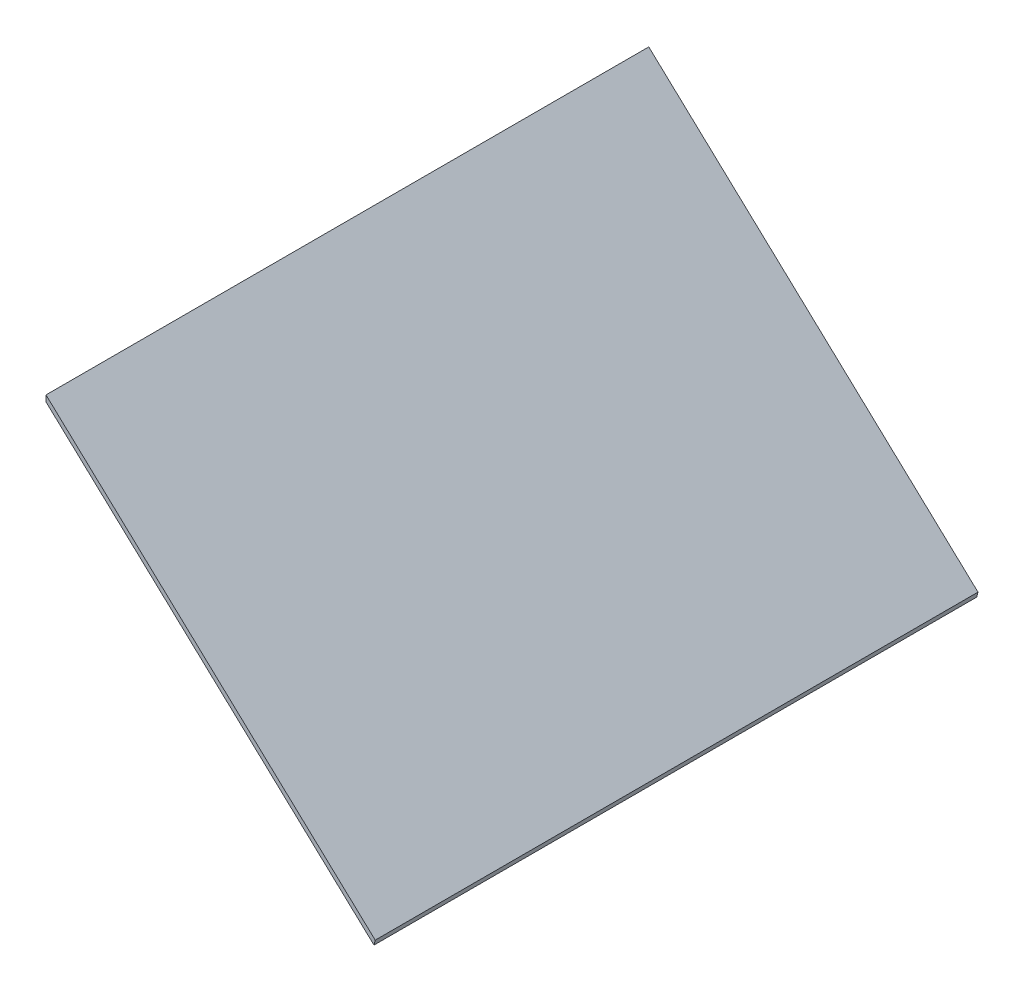
SolidWorks part; units mm, degrees
ref_plane "Front Plane" through (0, 0, 0) normal (0, 0, 1) x (1, 0, 0)
ref_plane "Top Plane" through (0, 0, 0) normal (0, 1, 0) x (1, 0, 0)
ref_plane "Right Plane" through (0, 0, 0) normal (1, 0, 0) x (0, 0, -1)
sketch "Sketch1" plane through (0, 0, 0) normal (0, 0, 1) x (1, 0, 0)
  line L0 (0, 0) -> (271.4553, 0) construction
  line L1 (271.4553, 0) -> (0, 253.5804)
  line L2 (0, 253.5804) -> (0, 0) construction
  line L3 (0, 253.5804) -> (0, 258.6284)
  line L4 (0, 258.6284) -> (272.483, 4.0878)
  line L5 (272.483, 4.0878) -> (271.4553, 0)
  point P3 (0, 249.9728)
  point P7 (279.4, 5.0479)
  point P8 (0, 290.91)
  point P9 (2.3851, 256.9301)
  point P10 (356.3459, 0)
  point P11 (271.4553, 0)
extrude "Boss-Extrude1" add sketch "Sketch1" along normal blind 498.856
